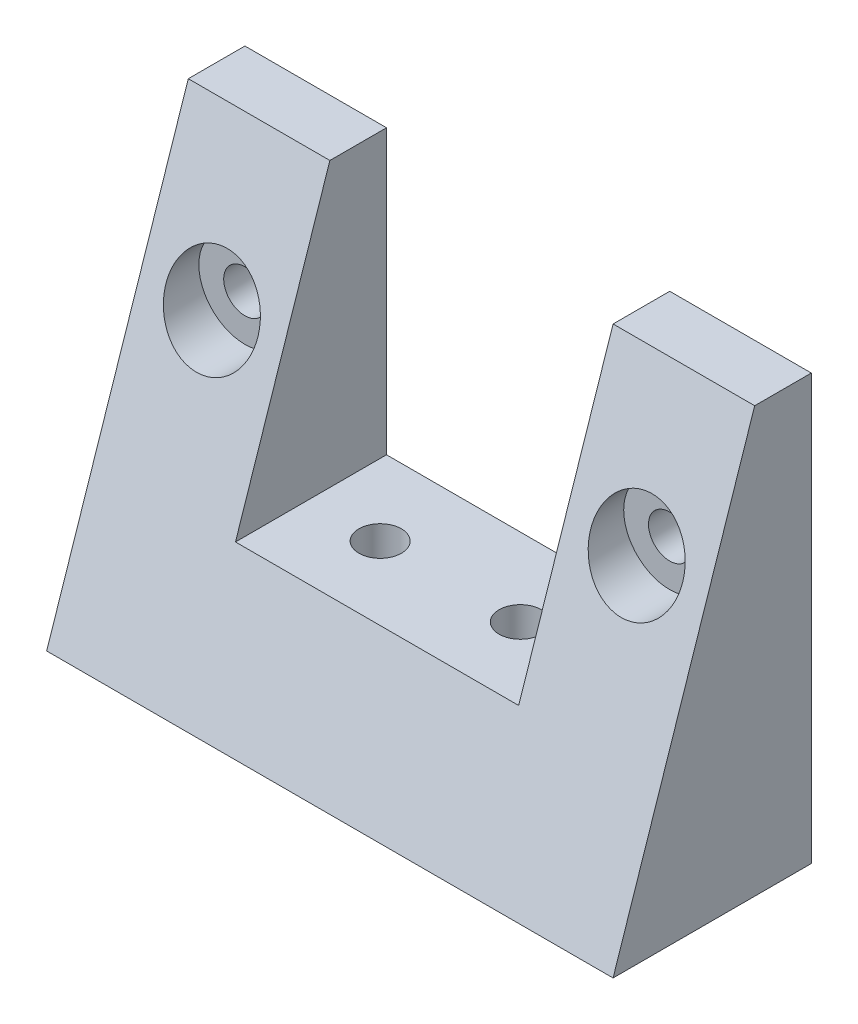
SolidWorks part; units mm, degrees
ref_plane "Спереди" through (0, 0, 0) normal (0, 0, 1) x (1, 0, 0)
ref_plane "Сверху" through (0, 0, 0) normal (0, 1, 0) x (1, 0, 0)
ref_plane "Справа" through (0, 0, 0) normal (1, 0, 0) x (0, 0, -1)
sketch "Sketch1" plane through (0, 0, 0) normal (1, 0, 0) x (0, 0, -1)
  line L0 (0, 0) -> (-14, 0)
  line L1 (-14, 0) -> (-4, 30)
  line L2 (-4, 30) -> (0, 30)
  line L3 (0, 30) -> (0, 0)
  dimension "D1" = 14
  dimension "D2" = 4
  dimension "D3" = 30
extrude "Extrude1" add sketch "Sketch1" against normal blind 40
sketch "Sketch2" plane through (0, 0, 0) normal (0, 0, -1) x (-1, 0, 0)
  line L0 (40, 30) -> (0, 30) construction
  line L1 (10, 30) -> (30, 30)
  line L2 (10, 30) -> (10, 10)
  line L3 (10, 10) -> (30, 10)
  line L4 (30, 30) -> (30, 10)
  line L5 (0, 0) -> (0, 30) construction
  line L6 (40, 0) -> (40, 30) construction
  line L7 (40, 0) -> (0, 0) construction
  dimension "D1" = 10
  dimension "D2" = 10
  dimension "D3" = 10
extrude "Extrude2" cut sketch "Sketch2" against normal through all
sketch "Sketch3" plane through (0, 0, 0) normal (0, 0, -1) x (-1, 0, 0)
  line L0 (10, 30) -> (10, 10) construction
  line L1 (10, 30) -> (0, 30) construction
  line L2 (20, 0) -> (20, 26.911) construction
  line L3 (40, 0) -> (0, 0) construction
  circle A0 centre (5, 20) radius 1.5
  circle A2 centre (35, 20) radius 1.5
  dimension "D1" = 3
  dimension "D2" = 5
  dimension "D3" = 10
extrude "Extrude3" cut sketch "Sketch3" against normal through all
sketch "Sketch4" plane through (0, 10, 0) normal (0, 1, 0) x (1, 0, 0)
  line L0 (-40, 0) -> (-30, 0) construction
  line L2 (-30, -10.6667) -> (-30, 0) construction
  line L3 (-20, -10.6667) -> (-20, 0) construction
  line L4 (-30, -10.6667) -> (-10, -10.6667) construction
  line L5 (-10, 0) -> (-30, 0) construction
  circle A0 centre (-24.95, -5.5) radius 1.5
  circle A1 centre (-15.05, -5.5) radius 1.5
  dimension "D1" = 5.5
  dimension "D2" = 3
  dimension "D3" = 5.05
extrude "Extrude4" cut sketch "Sketch4" against normal through all
ref_plane "Plane1" through (0, 0, 14) normal (0, 0, -1) x (-1, 0, 0)
sketch "Sketch8" plane through (0, 0, 14) normal (0, 0, -1) x (-1, 0, 0)
  line L7 (20, 0) -> (20, 29.8914) construction
  line L8 (40, 0) -> (0, 0) construction
  circle A0 centre (5, 20) radius 3.25
  circle A1 centre (35, 20) radius 3.25
  dimension "D1" = 6.5
extrude "Extrude5" cut sketch "Sketch8" along normal offset from surface (9 mm away) 5 up to face at (-5, 21.5, 0)
